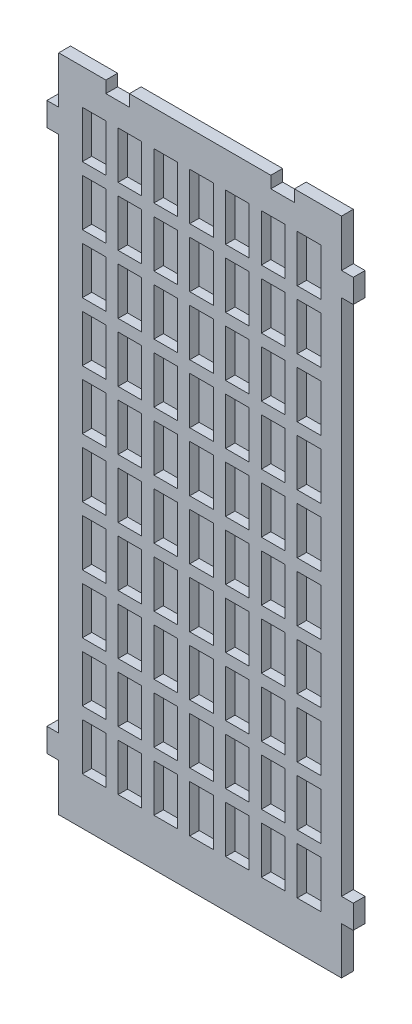
SolidWorks part; units mm, degrees
ref_plane "Front Plane" through (0, 0, 0) normal (0, 0, 1) x (1, 0, 0)
ref_plane "Top Plane" through (0, 0, 0) normal (0, 1, 0) x (1, 0, 0)
ref_plane "Right Plane" through (0, 0, 0) normal (1, 0, 0) x (0, 0, -1)
sketch "Sketch1" plane through (0, 0, 0) normal (0, 0, 1) x (1, 0, 0)
  line L0 (19.05, 0) -> (57.15, 0)
  line L1 (0, 0) -> (12.7, 0)
  line L2 (0, 0) -> (0, -12.7)
  line L3 (0, -177.8) -> (12.7, -177.8)
  line L4 (76.2, -19.05) -> (76.2, -158.75)
  line L5 (63.5, 0) -> (76.2, 0)
  line L6 (12.7, 0) -> (12.7, -3.175)
  line L7 (12.7, -3.175) -> (19.05, -3.175)
  line L8 (19.05, 0) -> (19.05, -3.175)
  line L9 (0, -19.05) -> (0, -158.75)
  line L10 (57.15, 0) -> (57.15, -3.175)
  line L11 (57.15, -3.175) -> (63.5, -3.175)
  line L12 (63.5, 0) -> (63.5, -3.175)
  line L13 (76.2, -12.7) -> (79.375, -12.7)
  line L14 (76.2, -165.1) -> (76.2, -177.8)
  line L15 (76.2, -19.05) -> (79.375, -19.05)
  line L16 (79.375, -12.7) -> (79.375, -19.05)
  line L17 (76.2, -158.75) -> (79.375, -158.75)
  line L18 (88.9, -177.8) -> (76.2, -177.8)
  line L19 (76.2, -165.1) -> (79.375, -165.1)
  line L20 (79.375, -158.75) -> (79.375, -165.1)
  line L21 (12.7, -177.8) -> (88.9, -177.8)
  line L25 (0, -165.1) -> (0, -177.8)
  line L29 (0, -165.1) -> (-3.175, -165.1)
  line L30 (63.5, 0) -> (76.2, 0)
  line L31 (0, -158.75) -> (-3.175, -158.75)
  line L32 (-3.175, -165.1) -> (-3.175, -158.75)
  line L33 (0, -19.05) -> (-3.175, -19.05)
  line L34 (76.2, 0) -> (76.2, -12.7)
  line L35 (0, -12.7) -> (-3.175, -12.7)
  line L36 (-3.175, -19.05) -> (-3.175, -12.7)
  dimension "D1" = 76.2
  dimension "D3" = 12.7
  dimension "D4" = 6.35
  dimension "D5" = 3.175
  dimension "D6" = 6.35
  dimension "D7" = 3.175
  dimension "D8" = 12.7
  dimension "D9" = 12.7
  dimension "D10" = 6.35
  dimension "D11" = 3.175
  dimension "D12" = 3.175
  dimension "D13" = 6.35
  dimension "D14" = 12.7
  dimension "D15" = 76.2
  dimension "D21" = 3.175
  dimension "D22" = 6.35
  dimension "D23" = 12.7
  dimension "D24" = 12.7
  dimension "D25" = 6.35
  dimension "D26" = 3.175
  dimension "D27" = 3.175
  dimension "D29" = 177.8
extrude "Boss-Extrude1" add sketch "Sketch1" along normal blind 3.175
sketch "Sketch2" plane through (0, 0, 3.175) normal (0, 0, 1) x (1, 0, 0)
  line L0 (12.7, -3.175) -> (19.05, -3.175) construction
  line L1 (6.35, -9.525) -> (12.7, -9.525)
  line L2 (6.35, -9.525) -> (6.35, -22.225)
  line L3 (6.35, -22.225) -> (12.7, -22.225)
  line L4 (12.7, -9.525) -> (12.7, -22.225)
  line L5 (6.35, -9.525) -> (12.7, -22.225) construction
  line L6 (6.35, -22.225) -> (12.7, -9.525) construction
  line L7 (0, -19.05) -> (0, -158.75) construction
  point P0 (9.525, -15.875)
  dimension "D1" = 6.35
  dimension "D2" = 6.35
  dimension "D3" = 12.7
  dimension "D4" = 6.35
extrude "Cut-Extrude1" cut sketch "Sketch2" against normal blind 2.54
pattern_linear "LPattern1" count 7 spacing 9.652 along (1, 0, 0) count 10 spacing 15.875 along (0, -1, 0) of "Cut-Extrude1"
